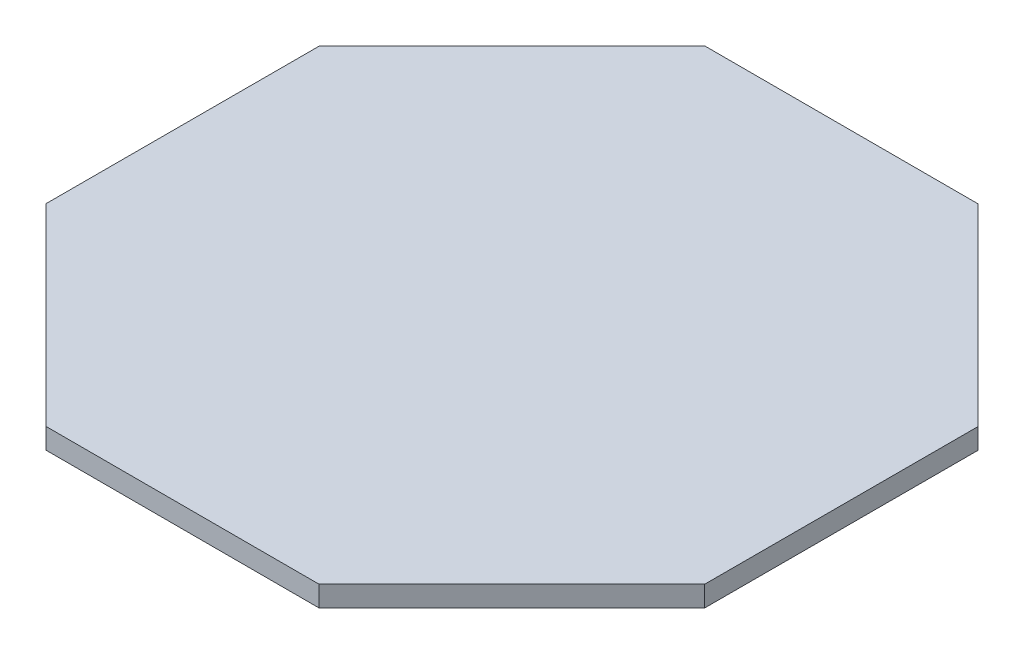
SolidWorks part; units mm, degrees
ref_plane "Front Plane" through (0, 0, 0) normal (0, 0, 1) x (1, 0, 0)
ref_plane "Top Plane" through (0, 0, 0) normal (0, 1, 0) x (1, 0, 0)
ref_plane "Right Plane" through (0, 0, 0) normal (1, 0, 0) x (0, 0, -1)
sketch "Sketch2" plane through (0, 0, 0) normal (0, 1, 0) x (1, 0, 0)
  line L1 (101.6211, 42.0331) -> (42.1351, 101.5789)
  line L2 (42.1351, 101.5789) -> (-42.0331, 101.6211)
  line L3 (-42.0331, 101.6211) -> (-101.5789, 42.1351)
  line L4 (-101.5789, 42.1351) -> (-101.6211, -42.0331)
  line L5 (-101.6211, -42.0331) -> (-42.1351, -101.5789)
  line L6 (-42.1351, -101.5789) -> (42.0331, -101.6211)
  line L7 (42.0331, -101.6211) -> (101.5789, -42.1351)
  line L8 (101.5789, -42.1351) -> (101.6211, 42.0331)
  circle A0 centre (0, 0) radius 101.6 construction
  dimension "D1" = 101.6
  dimension "D2" = 84.1682
extrude "Boss-Extrude3" add sketch "Sketch2" along normal blind 6.35 contours L6 L7 L8 L1 L2 L3 L4 L5
